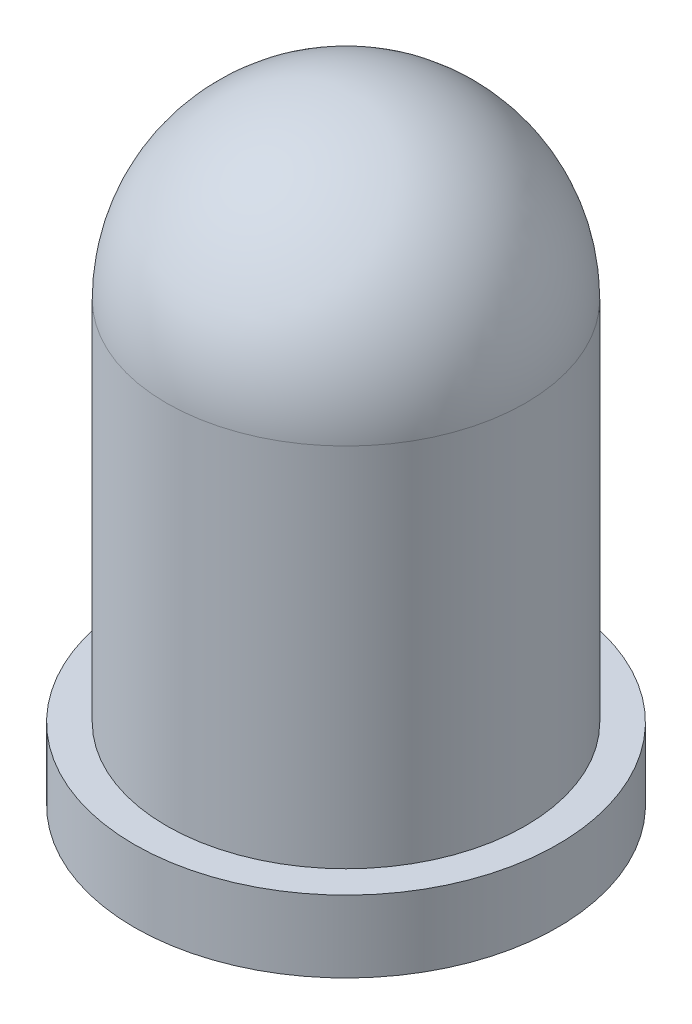
SolidWorks part; units mm, degrees
ref_plane "Plano frontal" through (0, 0, 0) normal (0, 0, 1) x (1, 0, 0)
ref_plane "Plano superior" through (0, 0, 0) normal (0, 1, 0) x (1, 0, 0)
ref_plane "Plano direito" through (0, 0, 0) normal (1, 0, 0) x (0, 0, -1)
sketch "Esboço1" plane through (0, 0, 0) normal (0, 1, 0) x (1, 0, 0)
  circle A0 centre (0, 0) radius 2.95
extrude "Ressalto-extrusão1" add sketch "Esboço1" along normal blind 1
sketch "Esboço2" plane through (0, 1, 0) normal (0, 1, 0) x (1, 0, 0)
  circle A0 centre (0, 0) radius 2.5
extrude "Ressalto-extrusão2" add sketch "Esboço2" along normal blind 7.6
fillet "Filete2" radius 2.5 1 edges at (0, 8.6, 2.5)
